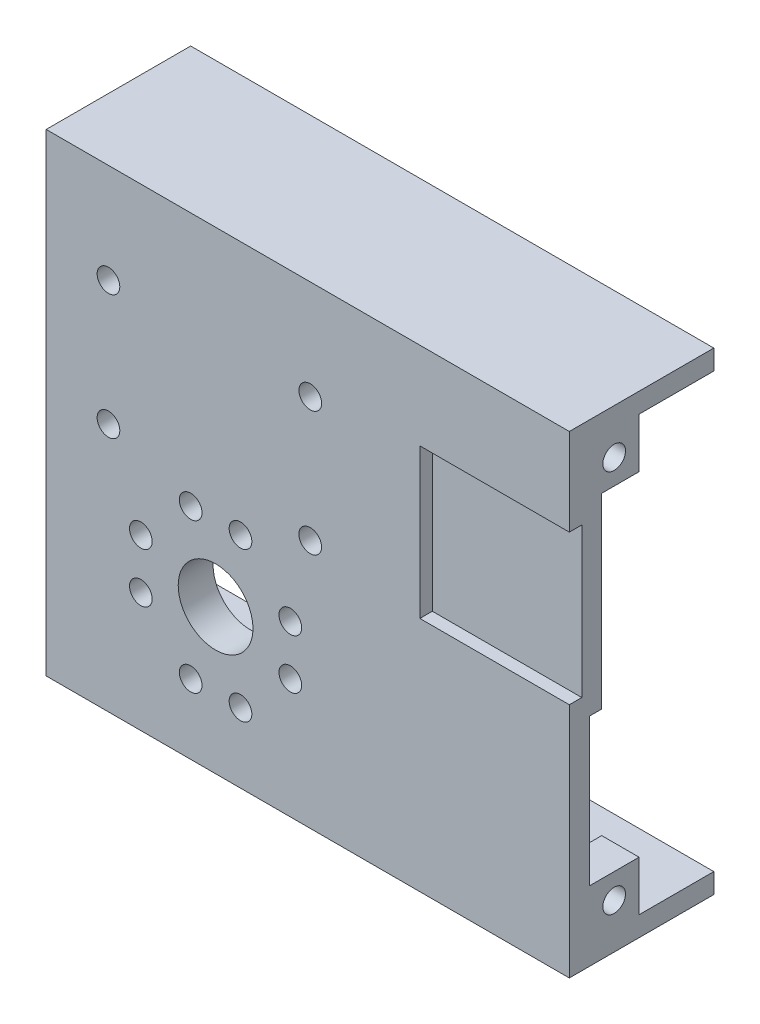
SolidWorks part; units mm, degrees
material "사용자정의 플라스틱"
ref_plane "정면" through (0, 0, 0) normal (0, 0, 1) x (1, 0, 0)
ref_plane "윗면" through (0, 0, 0) normal (0, 1, 0) x (1, 0, 0)
ref_plane "우측면" through (0, 0, 0) normal (1, 0, 0) x (0, 0, -1)
sketch "스케치1" plane through (0, 0, 0) normal (0, 0, 1) x (1, 0, 0)
  line L1 (-105, 95) -> (105, 95)
  line L2 (-105, 95) -> (-105, -95)
  line L3 (-105, -95) -> (105, -95)
  line L4 (105, 95) -> (105, -95)
  line L5 (-105, 95) -> (105, -95) construction
  line L6 (-105, -95) -> (105, 95) construction
  point P0 (0, 0)
  dimension "D1" = 210
  dimension "D2" = 190
extrude "보스-돌출1" add sketch "스케치1" along normal blind 8
sketch "스케치2" plane through (0, 0, 0) normal (0, 0, -1) x (-1, 0, 0)
  line L0 (-105, 95) -> (105, 95)
  line L1 (105, 95) -> (105, -95)
  line L2 (105, -95) -> (-105, -95)
  line L3 (-105, -95) -> (-105, -87)
  line L4 (-105, -95) -> (-105, 95) construction
  line L5 (-105, -87) -> (97, -87)
  line L6 (97, -87) -> (97, 87)
  line L7 (97, 87) -> (-105, 87)
  line L8 (-105, 87) -> (-105, 95)
  dimension "D1" = 8
  dimension "D2" = 8
  dimension "D3" = 8
extrude "보스-돌출2" add sketch "스케치2" along normal blind 50
sketch "스케치3" plane through (105, 0, 0) normal (1, 0, 0) x (0, 0, -1)
  line L1 (0, 87) -> (20, 87)
  line L2 (0, 87) -> (0, 67)
  line L3 (0, 67) -> (20, 67)
  line L4 (20, 87) -> (20, 67)
  dimension "D1" = 20
  dimension "D2" = 20
extrude "보스-돌출3" add sketch "스케치3" against normal blind 15
sketch "스케치8" plane through (105, 0, 0) normal (1, 0, 0) x (0, 0, -1)
  line L0 (0, 67) -> (20, 67) construction
  line L1 (20, 67) -> (20, 87) construction
  circle A0 centre (10, 77) radius 4.55
  dimension "D1" = 9.1
  dimension "D3" = 10
  dimension "D2" = 10
extrude "컷-돌출1" cut sketch "스케치8" against normal blind 25
ref_plane "평면1" through (0, 0, 0) normal (0, -1, 0) x (-1, 0, 0)
mirror "대칭 복사1" about plane through (0, 0, 0) normal (0, -1, 0) of "컷-돌출1", "보스-돌출3"
sketch "스케치9" plane through (0, 0, 0) normal (0, 0, -1) x (-1, 0, 0)
  line L1 (97, -87) -> (-23, -87)
  line L2 (97, -87) -> (97, 13)
  line L3 (97, 13) -> (-23, 13)
  line L4 (-23, -87) -> (-23, 13)
  dimension "D1" = 120
  dimension "D2" = 100
extrude "보스-돌출4" add sketch "스케치9" along normal blind 12
sketch "스케치10" plane through (0, 0, -12) normal (0, 0, -1) x (-1, 0, 0)
  line L6 (-23, 13) -> (-23, -87) construction
  line L9 (97, 13) -> (-23, 13) construction
  circle A0 centre (37, -37) radius 15
  dimension "D3" = 30
  dimension "D1" = 60
  dimension "D2" = 50
extrude "컷-돌출2" cut sketch "스케치10" against normal through all
sketch "스케치13" plane through (0, 0, 8) normal (0, 0, 1) x (1, 0, 0)
  circle A0 centre (-47, -7) radius 4.55
  circle A1 centre (-27, -7) radius 4.55
  circle A2 centre (-37, -37) radius 15 construction
  dimension "D1" = 9.1
  dimension "D2" = 9.1
  dimension "D4" = 30
  dimension "D6" = 10
  dimension "D3" = 10
  dimension "D5" = 30
extrude "컷-돌출3" cut sketch "스케치13" against normal through all
pattern_circular "원형 패턴2" count 4 over 360 about axis through (-37, -37, 0) along (0, 0, 1) of "컷-돌출3"
sketch "스케치14" plane through (0, 0, -12) normal (0, 0, -1) x (-1, 0, 0)
  line L1 (-23, 13) -> (97, 13)
  line L2 (-23, 13) -> (-23, -87)
  line L3 (-23, -87) -> (97, -87)
  line L4 (97, 13) -> (97, -87)
extrude "컷-돌출4" cut sketch "스케치14" against normal blind 6
sketch "스케치15" plane through (0, 0, 0) normal (0, 0, -1) x (-1, 0, 0)
  line L0 (-105, -67) -> (-105, 67) construction
  line L1 (-105, 68) -> (-37, 68)
  line L2 (-105, 68) -> (-105, -8)
  line L3 (-105, -8) -> (-37, -8)
  line L4 (-37, 68) -> (-37, -8)
  line L5 (-105, 68) -> (-37, -8) construction
  line L6 (-105, -8) -> (-37, 68) construction
  point P0 (-71, 30)
  dimension "D1" = 30
  dimension "D2" = 76
  dimension "D3" = 0
  dimension "D4" = 68
extrude "보스-돌출5" add sketch "스케치15" along normal blind 5
sketch "스케치16" plane through (0, 0, 8) normal (0, 0, 1) x (1, 0, 0)
  line L0 (105, -95) -> (105, 95) construction
  line L1 (105, 60) -> (45, 60)
  line L2 (105, 60) -> (105, 0)
  line L3 (105, 0) -> (45, 0)
  line L4 (45, 60) -> (45, 0)
  line L5 (105, -8) -> (37, -8) construction
  line L6 (37, 68) -> (90, 68) construction
  line L7 (37, -8) -> (37, 68) construction
  dimension "D1" = 8
  dimension "D2" = 8
  dimension "D3" = 8
extrude "컷-돌출5" cut sketch "스케치16" against normal blind 5
sketch "스케치17" plane through (0, 0, 8) normal (0, 0, 1) x (1, 0, 0)
  line L0 (-105, 95) -> (-105, -95) construction
  line L1 (105, 95) -> (-105, 95) construction
  circle A0 centre (1, 5.05) radius 4.55
  circle A1 centre (-80, 5.05) radius 4.55
  circle A2 centre (-80, 55.05) radius 4.55
  circle A3 centre (1, 55.05) radius 4.55
  dimension "D5" = 9.1
  dimension "D6" = 9.1
  dimension "D7" = 9.1
  dimension "D8" = 9.1
  dimension "D1" = 25
  dimension "D2" = 106
  dimension "D3" = 106
  dimension "D4" = 25
  dimension "D9" = 89.95
  dimension "D10" = 39.95
  dimension "D11" = 39.95
  dimension "D12" = 89.95
extrude "컷-돌출6" cut sketch "스케치17" against normal through all
sketch "스케치18" plane through (0, 0, -6) normal (0, 0, -1) x (-1, 0, 0)
  line L0 (97, 13) -> (-23, 13) construction
  line L1 (-23, 13) -> (17, 13)
  line L2 (-23, 13) -> (-23, -7)
  line L3 (-23, -7) -> (17, -7)
  line L4 (17, 13) -> (17, -7)
  line L5 (57, 13) -> (97, 13)
  line L6 (57, 13) -> (57, -7)
  line L7 (57, -7) -> (97, -7)
  line L8 (97, 13) -> (97, -7)
  line L9 (97, 87) -> (97, -87) construction
  dimension "D1" = 40
  dimension "D2" = 20
  dimension "D3" = 20
  dimension "D4" = 40
extrude "컷-돌출7" cut sketch "스케치18" against normal up to surface (6 mm away) up to face at (5.55, 55.05, 0)
